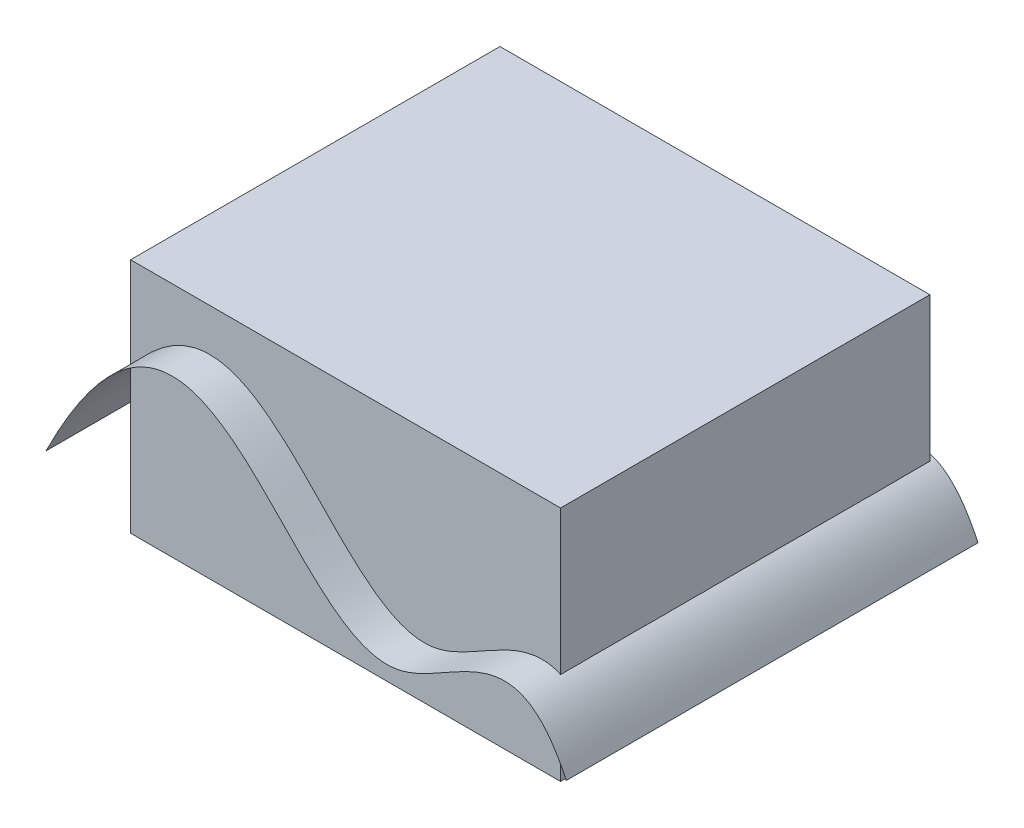
SolidWorks part; units mm, degrees
ref_plane "Front Plane" through (0, 0, 0) normal (0, 0, 1) x (1, 0, 0)
ref_plane "Top Plane" through (0, 0, 0) normal (0, 1, 0) x (1, 0, 0)
ref_plane "Right Plane" through (0, 0, 0) normal (1, 0, 0) x (0, 0, -1)
sketch "Sketch1" plane through (0, 0, 0) normal (0, 1, 0) x (1, 0, 0)
  line L1 (-72.9401, -62.6633) -> (72.9401, -62.6633)
  line L2 (-72.9401, -62.6633) -> (-72.9401, 62.6633)
  line L3 (-72.9401, 62.6633) -> (72.9401, 62.6633)
  line L4 (72.9401, -62.6633) -> (72.9401, 62.6633)
  line L5 (-72.9401, -62.6633) -> (72.9401, 62.6633) construction
  line L6 (-72.9401, 62.6633) -> (72.9401, -62.6633) construction
  point P0 (0, 0)
extrude "Boss-Extrude1" add sketch "Sketch1" along normal blind 80.3747
sketch "Sketch3" plane through (0, 0, 62.6633) normal (0, 0, 1) x (1, 0, 0)
  spline S0 degree 3 poles (-88.9504, 22.5455) (-37.8141, 125.2153) (5.8495, -43.718) (69.6437, 52.482) (87.5841, 13.9728) knots 0 0 0 0 0.665017 1 1 1 1
surface "Surface-Extrude1" sketch "Sketch3" parameters "D1"=127, "D2"=12.7
